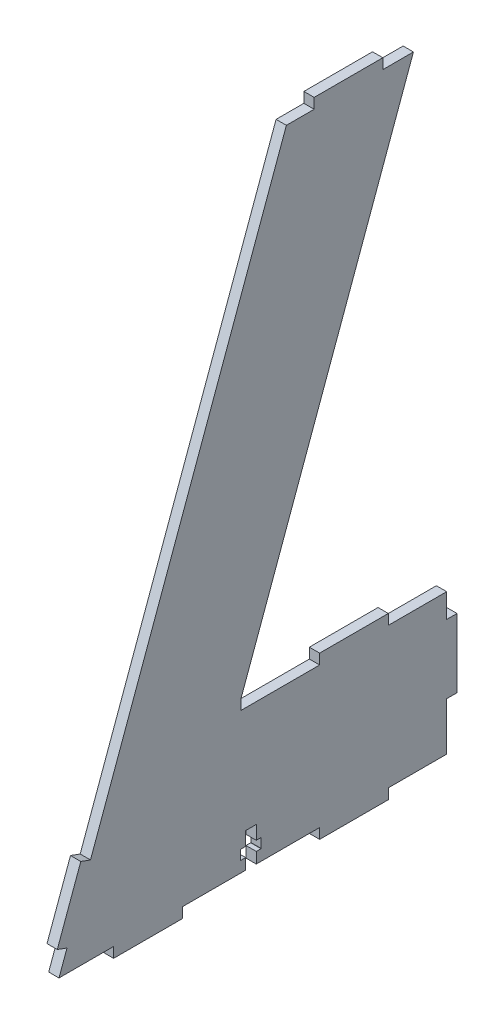
SolidWorks part; units mm, degrees
ref_plane "Front Plane" through (0, 0, 0) normal (0, 0, 1) x (1, 0, 0)
ref_plane "Top Plane" through (0, 0, 0) normal (0, 1, 0) x (1, 0, 0)
ref_plane "Right Plane" through (0, 0, 0) normal (1, 0, 0) x (0, 0, -1)
sketch "Sketch1" plane through (0, 0, 0) normal (1, 0, 0) x (0, 0, -1)
  line L0 (0, 0) -> (120, 0)
  line L1 (0, 0) -> (68.404, 187.9385)
  line L2 (120, 0) -> (188.404, 187.9385)
  line L3 (68.404, 187.9385) -> (188.404, 187.9385)
  dimension "D1" = 200
  dimension "D2" = 120
  dimension "D3" = 70
extrude "Boss-Extrude1" add sketch "Sketch1" along normal blind 3
sketch "Sketch2" plane through (3, 0, 0) normal (1, 0, 0) x (0, 0, -1)
  line L0 (188.404, 187.9385) -> (137.101, 46.9846)
  line L1 (188.404, 187.9385) -> (108.404, 187.9385)
  line L2 (137.101, 46.9846) -> (57.101, 46.9846)
  line L3 (108.404, 187.9385) -> (57.101, 46.9846)
  line L4 (120, 0) -> (188.404, 187.9385) construction
  dimension "D1" = 80
  dimension "D2" = 150
  dimension "D3" = 70
extrude "Cut-Extrude1" cut sketch "Sketch2" against normal through all
sketch "Sketch3" plane through (3, 0, 0) normal (1, 0, 0) x (0, 0, -1)
  line L1 (120, 0) -> (149.9768, 0)
  line L2 (120, 0) -> (120, 52.2685)
  line L3 (120, 52.2685) -> (149.9768, 52.2685)
  line L4 (149.9768, 0) -> (149.9768, 52.2685)
extrude "Cut-Extrude2" cut sketch "Sketch3" against normal through all
sketch "Sketch5" plane through (3, 0, 0) normal (1, 0, 0) x (0, 0, -1)
  line L0 (108.404, 187.9385) -> (68.404, 187.9385) construction
  line L1 (78.404, 187.9385) -> (67.3121, 187.9385)
  line L2 (78.404, 187.9385) -> (78.404, 184.9385)
  line L3 (78.404, 184.9385) -> (67.3121, 184.9385)
  line L4 (67.3121, 187.9385) -> (67.3121, 184.9385)
  line L5 (68.404, 187.9385) -> (0, 0) construction
  line L7 (108.404, 187.9385) -> (98.404, 187.9385)
  line L8 (108.404, 187.9385) -> (108.404, 184.9385)
  line L9 (108.404, 184.9385) -> (98.404, 184.9385)
  line L10 (98.404, 187.9385) -> (98.404, 184.9385)
  dimension "D1" = 3
  dimension "D2" = 10
  dimension "D3" = 3
  dimension "D4" = 10
  dimension "D5" = 20
extrude "Cut-Extrude4" cut sketch "Sketch5" against normal through all
sketch "Sketch6" plane through (3, 0, 0) normal (1, 0, 0) x (0, 0, -1)
  line L1 (120, 0) -> (100, 0)
  line L2 (120, 0) -> (120, 3)
  line L3 (120, 3) -> (100, 3)
  line L4 (100, 0) -> (100, 3)
  line L5 (0, 0) -> (20, 0)
  line L6 (0, 0) -> (0, 3)
  line L7 (0, 3) -> (20, 3)
  line L8 (20, 0) -> (20, 3)
  dimension "D1" = 3
  dimension "D2" = 3
  dimension "D3" = 20
  dimension "D4" = 20
extrude "Cut-Extrude5" cut sketch "Sketch6" against normal through all
sketch "Sketch7" plane through (3, 0, 0) normal (1, 0, 0) x (0, 0, -1)
  line L0 (20, 0) -> (100, 0) construction
  line L1 (40, 0) -> (80, 0)
  line L2 (40, 0) -> (40, 3)
  line L3 (40, 3) -> (80, 3)
  line L4 (80, 0) -> (80, 3)
  line L5 (20, 0) -> (20, 3) construction
  line L6 (100, 3) -> (100, 0) construction
  dimension "D1" = 3
  dimension "D2" = 40
  dimension "D3" = 20
  dimension "D4" = 20
extrude "Cut-Extrude6" cut sketch "Sketch7" against normal through all
sketch "Sketch8" plane through (3, 0, 0) normal (1, 0, 0) x (0, 0, -1)
  line L1 (120, 46.9846) -> (100, 46.9846)
  line L2 (120, 46.9846) -> (120, 43.9846)
  line L3 (120, 43.9846) -> (100, 43.9846)
  line L4 (100, 46.9846) -> (100, 43.9846)
  dimension "D1" = 3
  dimension "D2" = 20
extrude "Cut-Extrude7" cut sketch "Sketch8" against normal up to next
sketch "Sketch9" plane through (3, 0, 0) normal (1, 0, 0) x (0, 0, -1)
  line L0 (100, 46.9846) -> (100, 43.9846) construction
  line L1 (57.101, 46.9846) -> (80, 46.9846)
  line L2 (57.101, 46.9846) -> (57.101, 43.9846)
  line L3 (57.101, 43.9846) -> (80, 43.9846)
  line L4 (80, 46.9846) -> (80, 43.9846)
  dimension "D1" = 3
  dimension "D2" = 20
  dimension "D3" = 22.899
extrude "Cut-Extrude8" cut sketch "Sketch9" against normal up to next
sketch "Sketch10" plane through (3, 0, 0) normal (1, 0, 0) x (0, 0, -1)
  line L1 (120, 43.9846) -> (117, 43.9846)
  line L2 (120, 43.9846) -> (120, 36.9846)
  line L3 (120, 36.9846) -> (117, 36.9846)
  line L4 (117, 43.9846) -> (117, 36.9846)
  line L5 (120, 3) -> (117, 3)
  line L6 (120, 3) -> (120, 16.9846)
  line L7 (120, 16.9846) -> (117, 16.9846)
  line L8 (117, 3) -> (117, 16.9846)
  dimension "D1" = 3
  dimension "D2" = 3
  dimension "D3" = 7
  dimension "D4" = 20
extrude "Cut-Extrude9" cut sketch "Sketch10" against normal through all
sketch "Sketch11" plane through (3, 0, 0) normal (1, 0, 0) x (0, 0, -1)
  line L0 (67.3121, 184.9385) -> (1.0919, 3)
  line L1 (67.3121, 184.9385) -> (70.3121, 184.9385)
  line L2 (1.0919, 3) -> (4.0919, 3)
  line L3 (70.3121, 184.9385) -> (4.0919, 3)
  line L4 (20, 3) -> (1.0919, 3) construction
  dimension "D1" = 3
extrude "Cut-Extrude10" cut sketch "Sketch11" against normal blind 10
sketch "Sketch13" plane through (0, -0.9642, -2.6491) normal (0, 0.342, 0.9397) x (1, 0, 0)
  line L0 (0, 197.8335) -> (0, 4.2186) construction
  line L1 (0, 11.0261) -> (3, 11.0261)
  line L2 (0, 11.0261) -> (0, 31.0261)
  line L3 (0, 31.0261) -> (3, 31.0261)
  line L4 (3, 11.0261) -> (3, 31.0261)
  line L5 (3, 4.2186) -> (3, 197.8335) construction
  line L6 (3, 4.2186) -> (0, 4.2186) construction
  dimension "D1" = 20
  dimension "D2" = 6.8075
extrude "Boss-Extrude2" add sketch "Sketch13" along normal blind 3
sketch "Sketch14" plane through (3, 0, 0) normal (1, 0, 0) x (0, 0, -1)
  line L0 (80, 3) -> (40, 3) construction
  line L1 (58.45, 3) -> (61.55, 3)
  line L2 (58.45, 3) -> (58.45, 13)
  line L3 (58.45, 13) -> (61.55, 13)
  line L4 (61.55, 3) -> (61.55, 13)
  dimension "D1" = 3.1
  dimension "D2" = 18.45
  dimension "D3" = 10
extrude "Cut-Extrude11" cut sketch "Sketch14" against normal up to next
sketch "Sketch15" plane through (3, 0, 0) normal (1, 0, 0) x (0, 0, -1)
  line L0 (58.45, 13) -> (58.45, 3) construction
  line L1 (56.96, 9) -> (62.96, 9)
  line L2 (56.96, 9) -> (56.96, 6.2)
  line L3 (56.96, 6.2) -> (62.96, 6.2)
  line L4 (62.96, 9) -> (62.96, 6.2)
  line L6 (61.55, 13) -> (58.45, 13) construction
  line L7 (40, 0.0046) -> (80, 0.0046) construction
  dimension "D1" = 6
  dimension "D2" = 2.8
  dimension "D3" = 1.49
  dimension "D4" = 4
  dimension "D5" = 6.1954
extrude "Cut-Extrude12" cut sketch "Sketch15" against normal through all
sketch "Sketch16" plane through (3, 0, 0) normal (1, 0, 0) x (0, 0, -1)
  circle A0 centre (56.96, 6.2) radius 0.05
  dimension "D1" = 0.1
extrude "Cut-Extrude13" cut sketch "Sketch16" against normal through all
sketch "Sketch17" plane through (3, 0, 0) normal (1, 0, 0) x (0, 0, -1)
  circle A0 centre (62.96, 6.2) radius 0.05
  dimension "D1" = 0.1
extrude "Cut-Extrude14" cut sketch "Sketch17" against normal blind 10
